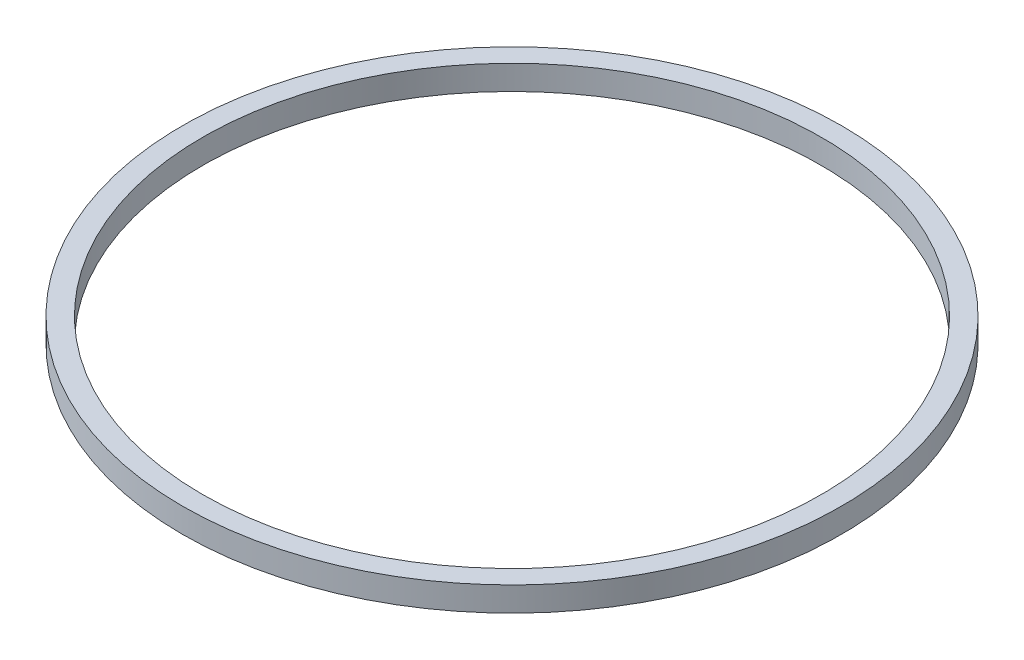
SolidWorks part; units mm, degrees
material "A-Glass Fiber"
ref_plane "Front Plane" through (0, 0, 0) normal (0, 0, 1) x (1, 0, 0)
ref_plane "Top Plane" through (0, 0, 0) normal (0, 1, 0) x (1, 0, 0)
ref_plane "Right Plane" through (0, 0, 0) normal (1, 0, 0) x (0, 0, -1)
sketch "Sketch1" plane through (0, 0, 0) normal (0, 1, 0) x (1, 0, 0)
  circle A0 centre (0, 0) radius 80.391
  circle A1 centre (0, 0) radius 85.6234
  dimension "D1" = 160.782
  dimension "D2" = 171.2468
extrude "Boss-Extrude1" add sketch "Sketch1" along normal blind 6.35
